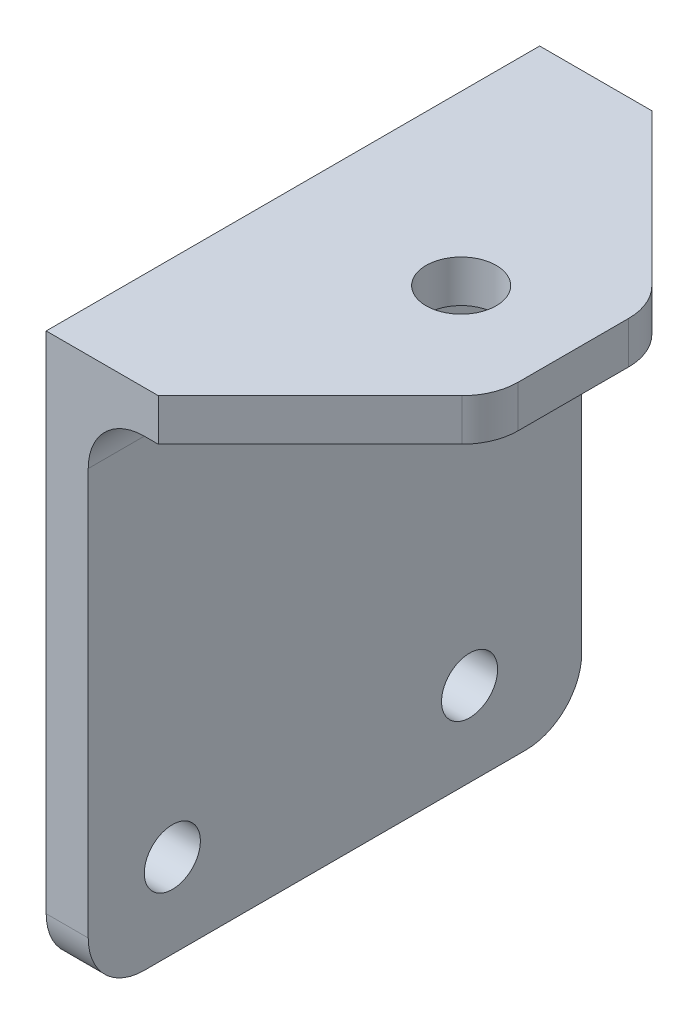
SolidWorks part; units mm, degrees
material "Plain Carbon Steel"
ref_plane "Front Plane" through (0, 0, 0) normal (0, 0, 1) x (1, 0, 0)
ref_plane "Top Plane" through (0, 0, 0) normal (0, 1, 0) x (1, 0, 0)
ref_plane "Right Plane" through (0, 0, 0) normal (1, 0, 0) x (0, 0, -1)
sketch "Sketch1" plane through (0, 0, 0) normal (0, 0, 1) x (1, 0, 0)
  line L0 (0, -63.5) -> (0, 0)
  line L1 (0, 0) -> (31.75, 0)
  line L2 (0, -63.5) -> (4.7625, -63.5)
  line L3 (4.7625, -63.5) -> (4.7625, -11.1125)
  line L4 (11.1125, -4.7625) -> (31.75, -4.7625)
  line L5 (31.75, -4.7625) -> (31.75, 0)
  arc A0 (4.7625, -11.1125) -> (11.1125, -4.7625) centre (11.1125, -11.1125) cw
  dimension "D4" = 6.35
  dimension "D1" = 63.5
  dimension "D2" = 31.75
  dimension "D3" = 4.7625
extrude "Boss-Extrude1" add sketch "Sketch1" along normal blind 55.88 contours L1 L5 L4 L3 L2 L0
sketch "Sketch2" plane through (0, 0, 0) normal (0, 1, 0) x (1, 0, 0)
  line L0 (0, -55.88) -> (0, 0) construction
  line L2 (31.75, -55.88) -> (0, -55.88) construction
  circle A0 centre (19.05, -27.94) radius 3.9688
  dimension "D1" = 7.9375
  dimension "D2" = 19.05
  dimension "D3" = 27.94
extrude "Cut-Extrude1" cut sketch "Sketch2" against normal blind 31.75
sketch "Sketch3" plane through (4.7625, 0, 0) normal (1, 0, 0) x (0, 0, -1)
  line L0 (-46.355, -53.975) -> (-12.7, -53.975) construction
  line L1 (-55.88, -63.5) -> (-55.88, -11.1125) construction
  line L2 (0, -63.5) -> (0, -11.1125) construction
  line L3 (-55.88, -63.5) -> (0, -63.5) construction
  circle A0 centre (-46.355, -53.975) radius 3.175
  circle A1 centre (-12.7, -53.975) radius 3.175
  dimension "D1" = 6.35
  dimension "D2" = 9.525
  dimension "D3" = 12.7
  dimension "D4" = 9.525
extrude "Cut-Extrude2" cut sketch "Sketch3" against normal blind 31.75
sketch "Sketch4" plane through (0, 0, 0) normal (0, 1, 0) x (1, 0, 0)
  line L0 (12.7, -55.88) -> (31.75, -36.83)
  line L1 (31.75, -55.88) -> (0, -55.88) construction
  line L2 (31.75, -55.88) -> (31.75, 0) construction
  line L3 (12.7, 0) -> (31.75, -19.05)
  line L4 (31.75, 0) -> (0, 0) construction
  line L5 (31.75, -19.05) -> (31.75, 0)
  line L6 (31.75, 0) -> (12.7, 0)
  line L7 (31.75, -36.83) -> (31.75, -55.88)
  line L8 (31.75, -55.88) -> (12.7, -55.88)
  point P18 (27.1683, -19.05)
  dimension "D1" = 19.05
  dimension "D2" = 45
extrude "Cut-Extrude3" cut sketch "Sketch4" against normal through all
fillet "Fillet2" radius 6.35 4 edges at (2.3813, -63.5, 0) (2.3813, -63.5, 55.88) (31.75, -2.3813, 36.83) (31.75, -2.3813, 19.05)
